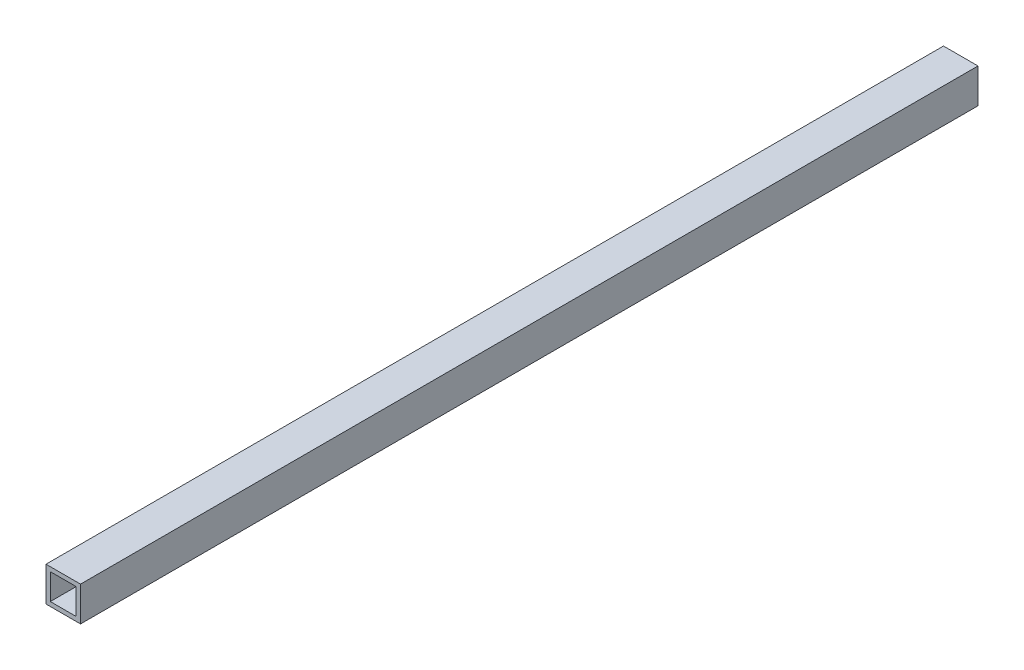
SolidWorks part; units mm, degrees
material "6061 Alloy"
ref_plane "Front Plane" through (0, 0, 0) normal (0, 0, 1) x (1, 0, 0)
ref_plane "Top Plane" through (0, 0, 0) normal (0, 1, 0) x (1, 0, 0)
ref_plane "Right Plane" through (0, 0, 0) normal (1, 0, 0) x (0, 0, -1)
sketch "Sketch1" plane through (0, 0, 0) normal (0, 0, 1) x (1, 0, 0)
  line L0 (12.7, 0) -> (9.525, 0) construction
  line L1 (-12.7, 0) -> (12.7, 0) construction
  line L2 (0, 12.7) -> (0, -12.7)
  point P7 (0, 0)
sketch "Sketch2" plane through (0, 0, 0) normal (1, 0, 0) x (0, 0, -1)
  line L0 (330.2, 0) -> (-330.2, 0)
  point P4 (0, 0)
  dimension "Length" = 660.4
sketch "Sketch3" plane through (0, 0, 0) normal (0, 0, 1) x (1, 0, 0)
  line L0 (-12.7, 0) -> (12.7, 0) construction
  line L5 (12.7, -12.7) -> (-12.7, -12.7)
  line L6 (12.7, -12.7) -> (12.7, 12.7)
  line L11 (12.7, 12.7) -> (-12.7, 12.7)
  line L12 (-12.7, -12.7) -> (-12.7, 12.7)
  line L14 (12.7, -12.7) -> (-12.7, 12.7) construction
  line L15 (12.7, 12.7) -> (-12.7, -12.7) construction
  line L16 (9.525, -9.525) -> (-9.525, -9.525)
  line L17 (9.525, -9.525) -> (9.525, 9.525)
  line L18 (9.525, 9.525) -> (-9.525, 9.525)
  line L19 (-9.525, -9.525) -> (-9.525, 9.525)
  line L20 (9.525, -9.525) -> (-9.525, 9.525) construction
  line L21 (9.525, 9.525) -> (-9.525, -9.525) construction
  point P0 (0, 0)
  point P5 (0, 0)
  point P13 (9.525, -12.7)
  dimension "D1" = 3.175
  dimension "D3" = 25.4
  dimension "D4" = 25.4
extrude "Boss-Extrude1" add sketch "Sketch3" along normal up to vertex (330.2 mm away) and the other way up to vertex (330.2 mm away) up to point (0, 0, 330.2) other way up to point (0, 0, -330.2)
sketch "Sketch5" plane through (0, 0, 0) normal (1, 0, 0) x (0, 0, -1)
  line L0 (-330.2, 0) -> (330.2, 0) construction
  line L3 (-330.2, -12.7) -> (-330.2, 12.7) construction
  line L4 (330.2, -12.7) -> (330.2, 12.7) construction
  point P6 (-301.625, 0)
  point P7 (-292.1, 0)
  point P8 (292.1, 0)
  point P10 (301.625, 0)
  dimension "D1" = 28.575
  dimension "D2" = 38.1
  dimension "D3" = 28.575
  dimension "D4" = 38.1
equation "\"D1@Sketch3\"=\"Wall thickness@Sketch1\""
equation "\"D1@Sketch5\"=\"Width@Sketch1\"*1.125"
equation "\"D2@Sketch5\"=\"Width@Sketch1\"*1.5"
equation "\"D3@Sketch5\"=\"D1@Sketch5\""
equation "\"D4@Sketch5\"=\"D2@Sketch5\""
equation "\"D2@Sketch3\"=\"Wall Thickness@Sketch1\""
